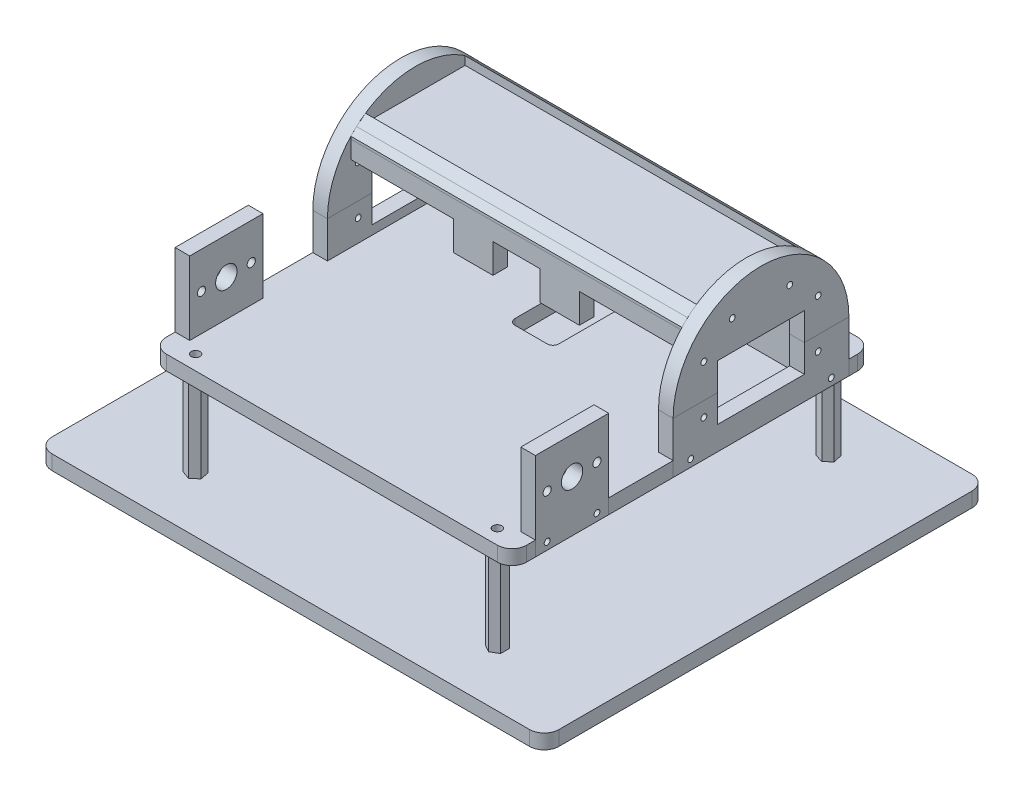
SolidWorks part; units mm, degrees
ref_plane "Plano frontal" through (0, 0, 0) normal (0, 0, 1) x (1, 0, 0)
ref_plane "Plano superior" through (0, 0, 0) normal (0, 1, 0) x (1, 0, 0)
ref_plane "Plano direito" through (0, 0, 0) normal (1, 0, 0) x (0, 0, -1)
sketch "Esboço1" plane through (0, 0, 0) normal (0, 1, 0) x (1, 0, 0)
  line L1 (-20.6889, 116.4867) -> (92.3111, 116.4867)
  line L2 (-25.6889, 111.4867) -> (-25.6889, -1.5133)
  line L3 (-20.6889, -6.5133) -> (92.3111, -6.5133)
  line L4 (97.3111, 111.4867) -> (97.3111, -1.5133)
  arc A0 (92.3111, -6.5133) -> (97.3111, -1.5133) centre (92.3111, -1.5133) ccw
  arc A1 (-20.6889, -6.5133) -> (-25.6889, -1.5133) centre (-20.6889, -1.5133) cw
  arc A2 (97.3111, 111.4867) -> (92.3111, 116.4867) centre (92.3111, 111.4867) ccw
  arc A3 (-25.6889, 111.4867) -> (-20.6889, 116.4867) centre (-20.6889, 111.4867) cw
  dimension "D1" = 5
extrude "Ressalto-extrusão1" add sketch "Esboço1" along normal blind 5
sketch "Esboço2" plane through (0, 5, 0) normal (0, 1, 0) x (1, 0, 0)
  line L0 (97.3111, -1.5133) -> (97.3111, 111.4867) construction
  line L1 (97.3111, 1.4867) -> (92.3111, 1.4867)
  line L2 (97.3111, 1.4867) -> (97.3111, 26.4867)
  line L3 (97.3111, 26.4867) -> (92.3111, 26.4867)
  line L4 (92.3111, 1.4867) -> (92.3111, 26.4867)
  line L5 (-20.6889, -6.5133) -> (92.3111, -6.5133) construction
  line L6 (-25.6889, 111.4867) -> (-25.6889, -1.5133) construction
  line L7 (-25.6889, 1.4867) -> (-20.6889, 1.4867)
  line L8 (-25.6889, 1.4867) -> (-25.6889, 26.4867)
  line L9 (-25.6889, 26.4867) -> (-20.6889, 26.4867)
  line L10 (-20.6889, 1.4867) -> (-20.6889, 26.4867)
  dimension "D1" = 8
  dimension "D2" = 8
extrude "Corte-extrusão1" cut sketch "Esboço2" against normal blind 5
sketch "Esboço4" plane through (0, 5, 0) normal (0, 1, 0) x (1, 0, 0)
  line L1 (97.3111, 1.4867) -> (92.3111, 1.4867)
  line L2 (97.3111, 1.4867) -> (97.3111, 26.4867)
  line L3 (97.3111, 26.4867) -> (92.3111, 26.4867)
  line L4 (92.3111, 1.4867) -> (92.3111, 26.4867)
  line L5 (-20.6889, 1.4867) -> (-25.6889, 1.4867)
  line L6 (-20.6889, 1.4867) -> (-20.6889, 26.4867)
  line L7 (-20.6889, 26.4867) -> (-25.6889, 26.4867)
  line L8 (-25.6889, 1.4867) -> (-25.6889, 26.4867)
extrude "Ressalto-extrusão2" add sketch "Esboço4" along normal blind 25 and the other way blind 5 separate body
sketch "Esboço5" plane through (97.3111, 0, 0) normal (1, 0, 0) x (0, 0, -1)
  line L1 (26.4867, 0) -> (26.4867, 5) construction
  line L2 (1.4867, 0) -> (26.4867, 0) construction
  line L3 (1.4867, 0) -> (1.4867, 5) construction
  line L4 (1.4867, 30) -> (26.4867, 30) construction
  line L5 (26.4867, 0) -> (26.4867, 30) construction
  circle A0 centre (5.4867, 2.5) radius 1
  circle A1 centre (22.4867, 2.5) radius 1
  circle A2 centre (13.9867, 17.5) radius 3.65
  circle A3 centre (5.4867, 17.5) radius 1.4
  circle A4 centre (22.4867, 17.5) radius 1.4
  dimension "D1" = 4
  dimension "D2" = 2.5
  dimension "D3" = 4
  dimension "D4" = 2.5
  dimension "D5" = 12.5
  dimension "D6" = 12.5
  dimension "D7" = 12.5
  dimension "D8" = 12.5
  dimension "D9" = 8.5
  dimension "D10" = 8.5
extrude "Corte-extrusão2" cut sketch "Esboço5" against normal blind 5
sketch "Esboço6" plane through (-25.6889, 0, 0) normal (-1, 0, 0) x (0, 0, 1)
  line L0 (-26.4867, 0) -> (-1.4867, 0) construction
  line L1 (-26.4867, 0) -> (-26.4867, 5) construction
  line L2 (-1.4867, 0) -> (-1.4867, 5) construction
  line L4 (-26.4867, 30) -> (-1.4867, 30) construction
  line L5 (-1.4867, 0) -> (-1.4867, 30) construction
  circle A0 centre (-22.4867, 2.5) radius 1
  circle A1 centre (-5.4867, 2.5) radius 1
  circle A2 centre (-13.9867, 17.5) radius 3.65
  circle A3 centre (-5.4867, 17.5) radius 1.4
  circle A4 centre (-22.4867, 17.5) radius 1.4
  point P14 (-26.4867, 2.5)
  dimension "D1" = 2.5
  dimension "D2" = 4
  dimension "D3" = 4
  dimension "D4" = 2.5
  dimension "D5" = 12.5
  dimension "D6" = 12.5
  dimension "D7" = 12.5
  dimension "D8" = 12.5
  dimension "D9" = 8.5
  dimension "D10" = 8.5
extrude "Corte-extrusão3" cut sketch "Esboço6" against normal blind 5
sketch "Esboço7" plane through (0, 5, 0) normal (0, 1, 0) x (1, 0, 0)
  line L0 (97.3111, 26.4867) -> (97.3111, 111.4867) construction
  line L1 (97.3111, 48.4867) -> (92.3111, 48.4867)
  line L2 (97.3111, 48.4867) -> (97.3111, 108.4867)
  line L3 (97.3111, 108.4867) -> (92.3111, 108.4867)
  line L4 (92.3111, 48.4867) -> (92.3111, 108.4867)
  line L5 (92.3111, 116.4867) -> (-20.6889, 116.4867) construction
  line L6 (-25.6889, 111.4867) -> (-25.6889, 26.4867) construction
  line L7 (-25.6889, 108.4867) -> (-20.6889, 108.4867)
  line L8 (-25.6889, 108.4867) -> (-25.6889, 48.4867)
  line L9 (-25.6889, 48.4867) -> (-20.6889, 48.4867)
  line L10 (-20.6889, 108.4867) -> (-20.6889, 48.4867)
  dimension "D1" = 8
extrude "Corte-extrusão4" cut sketch "Esboço7" against normal blind 5
sketch "Esboço8" plane through (0, 5, 0) normal (0, 1, 0) x (1, 0, 0)
  line L1 (97.3111, 48.4867) -> (92.3111, 48.4867)
  line L2 (97.3111, 48.4867) -> (97.3111, 108.4867)
  line L3 (97.3111, 108.4867) -> (92.3111, 108.4867)
  line L4 (92.3111, 48.4867) -> (92.3111, 108.4867)
  line L5 (-20.6889, 48.4867) -> (-25.6889, 48.4867)
  line L6 (-20.6889, 48.4867) -> (-20.6889, 108.4867)
  line L7 (-20.6889, 108.4867) -> (-25.6889, 108.4867)
  line L8 (-25.6889, 48.4867) -> (-25.6889, 108.4867)
extrude "Ressalto-extrusão3" add sketch "Esboço8" along normal blind 12.5 and the other way blind 5 separate body
sketch "Esboço9" plane through (97.3111, 0, 0) normal (1, 0, 0) x (0, 0, -1)
  line L4 (108.4867, 0) -> (108.4867, 17.5)
  line L5 (108.4867, 17.5) -> (48.4867, 17.5)
  line L6 (48.4867, 17.5) -> (48.4867, 0)
  line L7 (48.4867, 0) -> (108.4867, 0)
  line L9 (108.4867, 17.5) -> (48.4867, 17.5)
  arc A0 (48.4867, 17.5) -> (108.4867, 17.5) centre (78.4867, 17.5) cw
  dimension "D1" = 0
extrude "Ressalto-extrusão4" add sketch "Esboço9" against normal blind 5 separate body
sketch "Esboço10" plane through (-25.6889, 0, 0) normal (-1, 0, 0) x (0, 0, 1)
  line L4 (-48.4867, 0) -> (-48.4867, 17.5)
  line L5 (-48.4867, 17.5) -> (-108.4867, 17.5)
  line L6 (-108.4867, 17.5) -> (-108.4867, 0)
  line L7 (-108.4867, 0) -> (-48.4867, 0)
  line L9 (-48.4867, 17.5) -> (-108.4867, 17.5)
  arc A0 (-108.4867, 17.5) -> (-48.4867, 17.5) centre (-78.4867, 17.5) cw
  dimension "D1" = 0
extrude "Ressalto-extrusão5" add sketch "Esboço10" against normal blind 5 separate body contours A0 L9
sketch "Esboço11" plane through (-25.6889, 0, 0) normal (-1, 0, 0) x (0, 0, 1)
  line L1 (-93.2822, 26.95) -> (-63.6912, 26.95)
  line L2 (-93.2822, 26.95) -> (-93.2822, 8.1)
  line L3 (-93.2822, 8.1) -> (-63.6912, 8.1)
  line L4 (-63.6912, 26.95) -> (-63.6912, 8.1)
  line L6 (-108.4867, 0) -> (-48.4867, 0) construction
  line L7 (-48.4867, 0) -> (-48.4867, 17.5) construction
  line L8 (-108.4867, 0) -> (-108.4867, 17.5) construction
  dimension "D1" = 15.2045
  dimension "D2" = 15.2045
  dimension "D3" = 8.1
extrude "Corte-extrusão5" cut sketch "Esboço11" against normal blind 5
sketch "Esboço17" plane through (0, 5, 0) normal (0, 1, 0) x (1, 0, 0)
  line L0 (-20.6889, 48.4867) -> (-20.6889, 108.4867) construction
  line L1 (-20.6889, 56.4867) -> (92.3111, 56.4867)
  line L2 (-20.6889, 56.4867) -> (-20.6889, 61.4867)
  line L3 (-20.6889, 61.4867) -> (92.3111, 61.4867)
  line L4 (92.3111, 56.4867) -> (92.3111, 61.4867)
  line L5 (92.3111, 108.4867) -> (92.3111, 48.4867) construction
  line L6 (-25.6889, 48.4867) -> (-20.6889, 48.4867) construction
  dimension "D1" = 8
extrude "Ressalto-extrusão7" add sketch "Esboço17" along normal blind 32 separate body
sketch "Esboço22" plane through (0, 5, 0) normal (0, 1, 0) x (1, 0, 0)
  line L0 (-20.6889, 48.4867) -> (-20.6889, 108.4867) construction
  line L1 (-20.6889, 95.4867) -> (92.3111, 95.4867)
  line L2 (-20.6889, 95.4867) -> (-20.6889, 100.4867)
  line L3 (-20.6889, 100.4867) -> (92.3111, 100.4867)
  line L4 (92.3111, 95.4867) -> (92.3111, 100.4867)
  line L5 (92.3111, 108.4867) -> (92.3111, 48.4867) construction
  line L6 (97.3111, 108.4867) -> (92.3111, 108.4867) construction
  dimension "D1" = 8
extrude "Ressalto-extrusão10" add sketch "Esboço22" along normal blind 32 separate body
sketch "Esboço23" plane through (92.3111, 0, 0) normal (-1, 0, 0) x (0, 0, 1)
  line L0 (-95.4867, 37) -> (-95.4867, 5) construction
  line L1 (-95.4867, 39.32) -> (-61.4867, 39.32)
  line L2 (-95.4867, 39.32) -> (-95.4867, 34.32)
  line L3 (-95.4867, 34.32) -> (-61.4867, 34.32)
  line L4 (-61.4867, 39.32) -> (-61.4867, 34.32)
  line L5 (-61.4867, 37) -> (-61.4867, 5) construction
  arc A0 (-48.4867, 17.5) -> (-108.4867, 17.5) centre (-78.4867, 17.5) ccw construction
  point P11 (-78.4867, 47.5)
  dimension "D1" = 8.18
extrude "Ressalto-extrusão11" add sketch "Esboço23" along normal blind 113 separate body
sketch "Esboço24" plane through (92.3111, 0, 0) normal (-1, 0, 0) x (0, 0, 1)
  line L0 (-100.4867, 37) -> (-100.4867, 37.8666)
  line L1 (-100.4867, 37) -> (-95.4867, 37)
  line L2 (-95.4867, 37) -> (-95.4867, 42.1733)
  line L3 (-95.4867, 42.1733) -> (-96.1173, 41.7726)
  line L4 (-96.1173, 41.7726) -> (-98.5616, 39.7934)
  line L5 (-98.5616, 39.7934) -> (-100.4867, 37.8666)
  line L6 (-56.4867, 37) -> (-61.4867, 37)
  line L7 (-61.4867, 37) -> (-61.4867, 42.1733)
  line L8 (-61.4867, 42.1733) -> (-58.4117, 39.7934)
  line L9 (-58.4117, 39.7934) -> (-56.4867, 37.8684)
  line L10 (-56.4867, 37.8684) -> (-56.4867, 37)
  arc A0 (-48.4867, 17.5) -> (-108.4867, 17.5) centre (-78.4867, 17.5) ccw construction
extrude "Ressalto-extrusão12" add sketch "Esboço24" along normal blind 113 separate body
sketch "Esboço25" plane through (0, 0, -61.4867) normal (0, 0, -1) x (-1, 0, 0)
  line L0 (20.6889, 37) -> (20.6889, 5) construction
  line L1 (20.6889, 31) -> (-14.3111, 31)
  line L2 (20.6889, 31) -> (20.6889, 21)
  line L3 (20.6889, 21) -> (-14.3111, 21)
  line L4 (-14.3111, 31) -> (-14.3111, 21)
  line L5 (-92.3111, 37) -> (20.6889, 37) construction
  line L6 (-92.3111, 5) -> (20.6889, 5) construction
  line L7 (-92.3111, 37) -> (-92.3111, 5) construction
  line L9 (-92.3111, 26) -> (-92.3111, 16)
  dimension "D1" = 6
  dimension "D2" = 16
extrude "Corte-extrusão7" cut sketch "Esboço25" against normal blind 5 and the other way blind 39 contours L1 L4 L3 L2
sketch "Esboço26" plane through (0, 0, -61.4867) normal (0, 0, -1) x (-1, 0, 0)
  line L0 (-92.3111, 37) -> (-92.3111, 5) construction
  line L1 (-92.3111, 31) -> (-57.3111, 31)
  line L2 (-92.3111, 31) -> (-92.3111, 21)
  line L3 (-92.3111, 21) -> (-57.3111, 21)
  line L4 (-57.3111, 31) -> (-57.3111, 21)
  line L5 (-92.3111, 37) -> (20.6889, 37) construction
  line L6 (-92.3111, 5) -> (20.6889, 5) construction
  dimension "D1" = 6
  dimension "D2" = 16
extrude "Corte-extrusão8" cut sketch "Esboço26" against normal blind 5 and the other way blind 39
sketch "Esboço27" plane through (97.3111, 0, 0) normal (1, 0, 0) x (0, 0, -1)
  line L0 (48.4867, 0) -> (108.4867, 0) construction
  line L1 (63.6867, 26.95) -> (93.2867, 26.95)
  line L2 (63.6867, 26.95) -> (63.6867, 8.1)
  line L3 (63.6867, 8.1) -> (93.2867, 8.1)
  line L4 (93.2867, 26.95) -> (93.2867, 8.1)
  line L5 (48.4867, 0) -> (48.4867, 17.5) construction
  line L6 (108.4867, 0) -> (108.4867, 17.5) construction
  dimension "D1" = 8.1
  dimension "D2" = 15.2
  dimension "D3" = 15.2
extrude "Corte-extrusão9" cut sketch "Esboço27" against normal blind 5
sketch "Esboço28" plane through (-25.6889, 0, 0) normal (-1, 0, 0) x (0, 0, 1)
  line L0 (-108.4867, 0) -> (-108.4867, 17.5) construction
  line L1 (-108.4867, 0) -> (-48.4867, 0) construction
  line L2 (-48.4867, 0) -> (-48.4867, 17.5) construction
  line L3 (-93.2822, 26.95) -> (-93.2822, 17.5) construction
  line L4 (-63.6912, 26.95) -> (-63.6912, 17.5) construction
  line L5 (-108.4867, 0) -> (-108.4867, 5) construction
  line L6 (-48.4867, 0) -> (-48.4867, 5) construction
  circle A0 centre (-97.9867, 12.5) radius 1
  circle A1 centre (-97.9867, 29) radius 1
  circle A2 centre (-58.9867, 29) radius 1
  circle A3 centre (-58.9867, 12.5) radius 1
  circle A5 centre (-88.2822, 37) radius 1
  circle A6 centre (-68.6912, 37) radius 1
  arc A7 (-48.4867, 17.5) -> (-108.4867, 17.5) centre (-78.4867, 17.5) ccw construction
  circle A8 centre (-54.4867, 2.5) radius 1
  circle A9 centre (-102.4867, 2.5) radius 1
  dimension "D1" = 10.5
  dimension "D2" = 10.5
  dimension "D3" = 12.5
  dimension "D4" = 29
  dimension "D5" = 10.5
  dimension "D6" = 10.5
  dimension "D7" = 19.5
  dimension "D8" = 19.5
  dimension "D9" = 5
  dimension "D10" = 5
  dimension "D11" = 6
  dimension "D12" = 6
  dimension "D13" = 2.5
  dimension "D14" = 2.5
extrude "Corte-extrusão10" cut sketch "Esboço28" against normal blind 5
sketch "Esboço29" plane through (97.3111, 0, 0) normal (1, 0, 0) x (0, 0, -1)
  line L0 (48.4867, 0) -> (48.4867, 17.5) construction
  line L1 (48.4867, 0) -> (108.4867, 0) construction
  line L2 (108.4867, 0) -> (108.4867, 5) construction
  line L3 (108.4867, 0) -> (108.4867, 17.5) construction
  line L4 (63.6867, 26.95) -> (63.6867, 17.5) construction
  line L6 (93.2867, 26.95) -> (93.2867, 17.5) construction
  circle A0 centre (54.4867, 2.5) radius 1
  circle A1 centre (102.4867, 2.5) radius 1
  circle A2 centre (58.9867, 12.5) radius 1
  circle A3 centre (58.9867, 29) radius 1
  circle A4 centre (68.6867, 37) radius 1
  circle A5 centre (88.2867, 37) radius 1
  circle A6 centre (97.9867, 29) radius 1
  circle A7 centre (97.9867, 12.5) radius 1
  arc A9 (108.4867, 17.5) -> (48.4867, 17.5) centre (78.4867, 17.5) ccw construction
  point P26 (63.6867, 22.225)
  dimension "D1" = 6
  dimension "D2" = 2.5
  dimension "D3" = 6
  dimension "D4" = 2.5
  dimension "D5" = 10.5
  dimension "D7" = 10.5
  dimension "D8" = 12.5
  dimension "D9" = 10.5
  dimension "D10" = 29
  dimension "D11" = 10.5
  dimension "D12" = 29
  dimension "D13" = 5
  dimension "D14" = 19.5
  dimension "D15" = 5
  dimension "D16" = 19.5
  dimension "D6" = 12.5
extrude "Corte-extrusão11" cut sketch "Esboço29" against normal blind 5
sketch "Esboço31" plane through (0, 0, -100.4867) normal (0, 0, -1) x (-1, 0, 0)
  line L0 (20.6889, 21) -> (20.6889, 5) construction
  line L1 (-92.3111, 21) -> (-92.3111, 5) construction
  line L3 (-92.3111, 5) -> (20.6889, 5) construction
  circle A0 centre (-17.1411, 13) radius 1.6255
  circle A1 centre (-54.4811, 13) radius 1.6255
  dimension "D1" = 37.34
  dimension "D2" = 37.83
  dimension "D3" = 37.83
  dimension "D4" = 8
extrude "Corte-extrusão12" cut sketch "Esboço31" against normal blind 10
sketch "Esboço32" plane through (0, 0, 0) normal (0, -1, 0) x (1, 0, 0)
  line L0 (92.3111, -116.4867) -> (-20.6889, -116.4867) construction
  line L1 (30.3111, -111.4867) -> (41.3111, -111.4867)
  line L2 (28.3111, -109.4867) -> (28.3111, -63.4867)
  line L3 (30.3111, -61.4867) -> (41.3111, -61.4867)
  line L4 (43.3111, -109.4867) -> (43.3111, -63.4867)
  line L5 (-20.6889, -48.4867) -> (-20.6889, -108.4867) construction
  line L6 (92.3111, -108.4867) -> (92.3111, -48.4867) construction
  arc A0 (43.3111, -63.4867) -> (41.3111, -61.4867) centre (41.3111, -63.4867) ccw
  arc A1 (30.3111, -61.4867) -> (28.3111, -63.4867) centre (30.3111, -63.4867) ccw
  arc A2 (30.3111, -111.4867) -> (28.3111, -109.4867) centre (30.3111, -109.4867) cw
  arc A3 (41.3111, -111.4867) -> (43.3111, -109.4867) centre (41.3111, -109.4867) ccw
  dimension "D4" = 2
  dimension "D1" = 5
  dimension "D2" = 49
  dimension "D3" = 49
extrude "Corte-extrusão13" cut sketch "Esboço32" against normal blind 5
sketch "Esboço33" plane through (0, 0, -56.4867) normal (0, 0, 1) x (1, 0, 0)
  line L1 (43.8111, 21) -> (27.8111, 21)
  line L2 (43.8111, 21) -> (43.8111, 31)
  line L3 (43.8111, 31) -> (27.8111, 31)
  line L4 (27.8111, 21) -> (27.8111, 31)
  line L6 (-20.6889, 5) -> (92.3111, 5) construction
  line L7 (-20.6889, 37) -> (92.3111, 37) construction
  line L8 (57.3111, 21) -> (57.3111, 31) construction
  line L9 (14.3111, 31) -> (14.3111, 21) construction
  dimension "D1" = 16
  dimension "D2" = 6
  dimension "D3" = 13.5
  dimension "D4" = 13.5
extrude "Corte-extrusão14" cut sketch "Esboço33" against normal blind 5
sketch "Esboço34" plane through (0, 0, 0) normal (0, -1, 0) x (1, 0, 0)
  line L0 (-20.6889, 6.5133) -> (92.3111, 6.5133) construction
  line L1 (87.3111, 4.5133) -> (84.713, 3.0133)
  line L2 (84.713, 3.0133) -> (84.713, 0.0133)
  line L3 (84.713, 0.0133) -> (87.3111, -1.4867)
  line L4 (87.3111, -1.4867) -> (89.9091, 0.0133)
  line L5 (89.9091, 0.0133) -> (89.9091, 3.0133)
  line L6 (89.9091, 3.0133) -> (87.3111, 4.5133)
  line L7 (97.3111, 1.5133) -> (97.3111, -1.4867) construction
  line L8 (-25.6889, -1.4867) -> (-25.6889, 1.5133) construction
  line L9 (-13.4206, -0.4499) -> (-12.8545, 2.4962)
  line L10 (-12.8545, 2.4962) -> (-15.1229, 4.4595)
  line L11 (-15.1229, 4.4595) -> (-17.9573, 3.4766)
  line L12 (-17.9573, 3.4766) -> (-18.5234, 0.5305)
  line L13 (-18.5234, 0.5305) -> (-16.255, -1.4328)
  line L14 (-16.255, -1.4328) -> (-13.4206, -0.4499)
  line L15 (97.3111, -108.4867) -> (97.3111, -111.4867) construction
  line L16 (87.97, -108.5599) -> (85.1059, -109.4526)
  line L17 (85.1059, -109.4526) -> (84.4469, -112.3794)
  line L18 (84.4469, -112.3794) -> (86.6521, -114.4134)
  line L19 (86.6521, -114.4134) -> (89.5162, -113.5207)
  line L20 (89.5162, -113.5207) -> (90.1752, -110.594)
  line L21 (90.1752, -110.594) -> (87.97, -108.5599)
  line L22 (92.3111, -116.4867) -> (-20.6889, -116.4867) construction
  line L23 (-25.6889, -111.4867) -> (-25.6889, -108.4867) construction
  line L24 (-18.4806, -110.3881) -> (-18.0362, -113.355)
  line L25 (-18.0362, -113.355) -> (-15.2446, -114.4536)
  line L26 (-15.2446, -114.4536) -> (-12.8973, -112.5853)
  line L27 (-12.8973, -112.5853) -> (-13.3417, -109.6184)
  line L28 (-13.3417, -109.6184) -> (-16.1333, -108.5198)
  line L29 (-16.1333, -108.5198) -> (-18.4806, -110.3881)
  circle A0 centre (87.3111, 1.5133) radius 3 construction
  circle A1 centre (-15.6889, 1.5133) radius 3 construction
  circle A2 centre (87.3111, -111.4867) radius 3 construction
  circle A3 centre (-15.6889, -111.4867) radius 3 construction
  point P12 (97.3111, 0.0133)
  point P23 (-25.6889, 0.0133)
  dimension "D1" = 5
  dimension "D2" = 10
  dimension "D3" = 10
  dimension "D4" = 5
  dimension "D5" = 10
  dimension "D6" = 5
  dimension "D7" = 10
  dimension "D8" = 5
extrude "Ressalto-extrusão13" add sketch "Esboço34" along normal blind 30 separate body contours L28 L29 L24 L25 L26 L27 | L20 L21 L16 L17 L18 L19 | L4 L5 L6 L1 L2 L3 | L14 L9 L10 L11 L12 L13
sketch "Esboço35" plane through (0, -30, 0) normal (0, -1, 0) x (1, 0, 0)
  line L0 (85.1059, -109.4526) -> (84.4469, -112.3794) construction
  line L1 (89.5162, -113.5207) -> (90.1752, -110.594) construction
  circle A0 centre (87.2781, -111.6242) radius 1.5
  circle A1 centre (-15.7059, -111.6242) radius 1.5
  circle A2 centre (-15.7059, 1.4574) radius 1.5
  circle A3 centre (87.2781, 1.4574) radius 1.5
  point P7 (84.7764, -110.916)
  dimension "D1" = 2.6
  dimension "D2" = 2.6
extrude "Ressalto-extrusão14" add sketch "Esboço35" along normal blind 6 separate body
sketch "Esboço36" plane through (0, 5, 0) normal (0, 1, 0) x (1, 0, 0)
  line L0 (97.3111, -1.5133) -> (97.3111, 1.4867) construction
  line L1 (-20.6889, -6.5133) -> (92.3111, -6.5133) construction
  line L2 (-25.6889, 1.4867) -> (-25.6889, -1.5133) construction
  line L3 (92.3111, 116.4867) -> (-20.6889, 116.4867) construction
  line L4 (-25.6889, 111.4867) -> (-25.6889, 108.4867) construction
  line L5 (97.3111, 108.4867) -> (97.3111, 111.4867) construction
  circle A0 centre (87.3111, -1.5133) radius 1.5
  circle A1 centre (-15.6889, -1.5133) radius 1.5
  circle A2 centre (-15.6889, 111.4867) radius 1.5
  circle A3 centre (87.3111, 111.4867) radius 1.5
  dimension "D1" = 10
  dimension "D2" = 5
  dimension "D3" = 5
  dimension "D4" = 10
  dimension "D5" = 5
  dimension "D6" = 10
  dimension "D7" = 10
  dimension "D8" = 5
extrude "Corte-extrusão15" cut sketch "Esboço36" against normal blind 10
sketch "Esboço38" plane through (0, -30, 0) normal (0, -1, 0) x (1, 0, 0)
  line L0 (97.3111, -1.4867) -> (97.3111, -26.4867) construction
  line L1 (-45.6889, 20.5133) -> (117.3111, 20.5133)
  line L2 (-50.6889, 15.5133) -> (-50.6889, -125.4867)
  line L3 (-45.6889, -130.4867) -> (117.3111, -130.4867)
  line L4 (122.3111, 15.5133) -> (122.3111, -125.4867)
  line L7 (-20.6889, 6.5133) -> (92.3111, 6.5133) construction
  line L8 (-25.6889, -10.3367) -> (-25.6889, -17.6367) construction
  arc A0 (122.3111, 15.5133) -> (117.3111, 20.5133) centre (117.3111, 15.5133) ccw
  arc A1 (117.3111, -130.4867) -> (122.3111, -125.4867) centre (117.3111, -125.4867) ccw
  arc A2 (-45.6889, -130.4867) -> (-50.6889, -125.4867) centre (-45.6889, -125.4867) cw
  arc A3 (-45.6889, 20.5133) -> (-50.6889, 15.5133) centre (-45.6889, 15.5133) ccw
  dimension "D4" = 5
  dimension "D1" = 25
  dimension "D2" = 14
  dimension "D3" = 25
extrude "Ressalto-extrusão15" add sketch "Esboço38" along normal blind 5 separate body
sketch "Esboço40" plane through (0, 0, -56.4867) normal (0, 0, 1) x (1, 0, 0)
  line L0 (-20.6889, 21) -> (14.3111, 21) construction
  line L1 (-20.6889, 21) -> (92.3111, 21)
  line L2 (-20.6889, 21) -> (-20.6889, 5)
  line L3 (-20.6889, 5) -> (92.3111, 5)
  line L4 (92.3111, 21) -> (92.3111, 5)
  line L5 (-20.6889, 5) -> (92.3111, 5) construction
  line L6 (-20.6889, 21) -> (-20.6889, 5) construction
  dimension "D1" = 0
extrude "Corte-extrusão16" cut sketch "Esboço40" against normal blind 5
